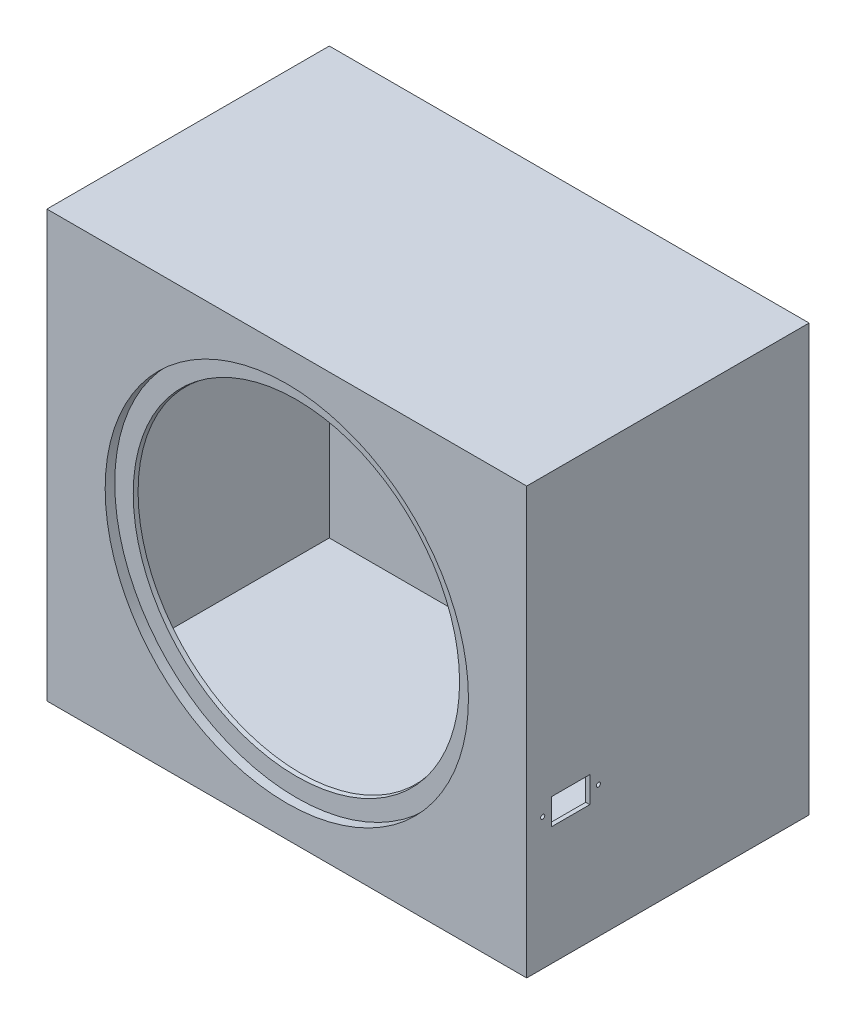
SolidWorks part; units mm, degrees
ref_plane "Front Plane" through (0, 0, 0) normal (0, 0, 1) x (1, 0, 0)
ref_plane "Top Plane" through (0, 0, 0) normal (0, 1, 0) x (1, 0, 0)
ref_plane "Right Plane" through (0, 0, 0) normal (1, 0, 0) x (0, 0, -1)
sketch "Sketch1" plane through (0, 0, 0) normal (0, 0, 1) x (1, 0, 0)
  line L1 (150, 152.4) -> (-150, 152.4)
  line L2 (150, 152.4) -> (150, -152.4)
  line L3 (150, -152.4) -> (-150, -152.4)
  line L4 (-150, 152.4) -> (-150, -152.4)
  line L5 (0, -152.4) -> (0, 152.4) construction
  line L6 (150, 0) -> (-150, 0) construction
  circle A0 centre (0, 0) radius 132 construction
  point P6 (0, -152.4)
  point P7 (-152.4, 0)
  point P8 (0, -243.486)
  point P9 (-152.4, 0)
  point P10 (152.4, 0)
  point P11 (351.5153, -157.0248)
  point P12 (0, -160.7655)
  point P13 (0, 0)
  dimension "D1" = 264
  dimension "D2" = 300
  dimension "D4" = 152.4
extrude "Boss-Extrude1" add sketch "Sketch1" against normal blind 200
sketch "Sketch7" plane through (0, -152.4, 0) normal (0, -1, 0) x (1, 0, 0)
  line L0 (-172, -200) -> (-172, -127.5)
  line L1 (-172, -127.5) -> (-172, 0)
  line L2 (-172, 0) -> (172, 0)
  line L3 (172, 0) -> (172, -127.5)
  line L4 (172, -127.5) -> (172, -200)
  line L5 (172, -200) -> (-172, -200)
  line L6 (0, -200) -> (0, 0) construction
  line L7 (-150, -200) -> (150, -200) construction
  point P8 (0, 0)
  point P10 (0, -200)
  dimension "D2" = 344
extrude "Boss-Extrude3" add sketch "Sketch7" against normal through all
sketch "Sketch2" plane through (0, 0, 0) normal (0, 1, 0) x (1, 0, 0)
  line L0 (0, 0) -> (0, 45) construction
  line L1 (172, 0) -> (-172, 0) construction
  line L2 (0, 0) -> (135.5, 0)
  line L3 (135.5, 0) -> (135.5, 7)
  line L4 (135.5, 7) -> (118.5, 7)
  line L5 (118.5, 7) -> (111.7996, 45)
  line L6 (111.7996, 45) -> (0, 45)
  line L7 (0, 0) -> (0, 45)
  point P4 (112.0182, 45)
  dimension "D1" = 271
  dimension "D2" = 7
  dimension "D3" = 45
  dimension "D4" = 80
  dimension "D5" = 17
revolve "Cut-Revolve1" cut sketch "Sketch2" angle 360 about L0
shell "Shell1" thickness 3
sketch "Sketch8" plane through (-175, 0, 0) normal (-1, 0, 0) x (0, 0, 1)
  line L0 (-40.65, -121.75) -> (-40.65, -140.4) construction
  line L1 (-22, -121.75) -> (-22, -140.4) construction
  line L2 (-40.65, -131.075) -> (-22, -131.075) construction
  line L3 (3, 155.4) -> (3, -155.4) construction
  line L4 (3, -155.4) -> (-203, -155.4) construction
  circle A0 centre (-40.65, -121.75) radius 2.65
  circle A1 centre (-22, -121.75) radius 2.65
  circle A2 centre (-22, -140.4) radius 2.65
  circle A3 centre (-40.65, -140.4) radius 2.65
  point P10 (-12.2201, -136.4765)
  dimension "D3" = 5.3
  dimension "D1" = 18.65
  dimension "D2" = 18.65
  dimension "D4" = 25
  dimension "D5" = 15
extrude "Cut-Extrude3" cut sketch "Sketch8" against normal up to next
sketch "Sketch9" plane through (175, 0, 0) normal (1, 0, 0) x (0, 0, -1)
  line L0 (8.68, -59.4) -> (15, -59.4) construction
  line L1 (15, -49.9) -> (43, -49.9)
  line L2 (15, -49.9) -> (15, -68.9)
  line L3 (15, -68.9) -> (43, -68.9)
  line L4 (43, -49.9) -> (43, -68.9)
  line L5 (29, -68.9) -> (29, -49.9) construction
  line L6 (15, -59.4) -> (43, -59.4) construction
  line L7 (43, -59.4) -> (49.32, -59.4) construction
  line L8 (-3, 155.4) -> (-3, -155.4) construction
  line L9 (203, -155.4) -> (-3, -155.4) construction
  circle A0 centre (8.68, -59.4) radius 1.5
  circle A1 centre (49.32, -59.4) radius 1.5
  point P8 (29.0012, -120.444)
  point P200 (29, -59.4)
  dimension "D3" = 40.64
  dimension "D4" = 3
  dimension "D1" = 28
  dimension "D2" = 19
  dimension "D5" = 32
  dimension "D6" = 96
extrude "Cut-Extrude4" cut sketch "Sketch9" against normal up to next
